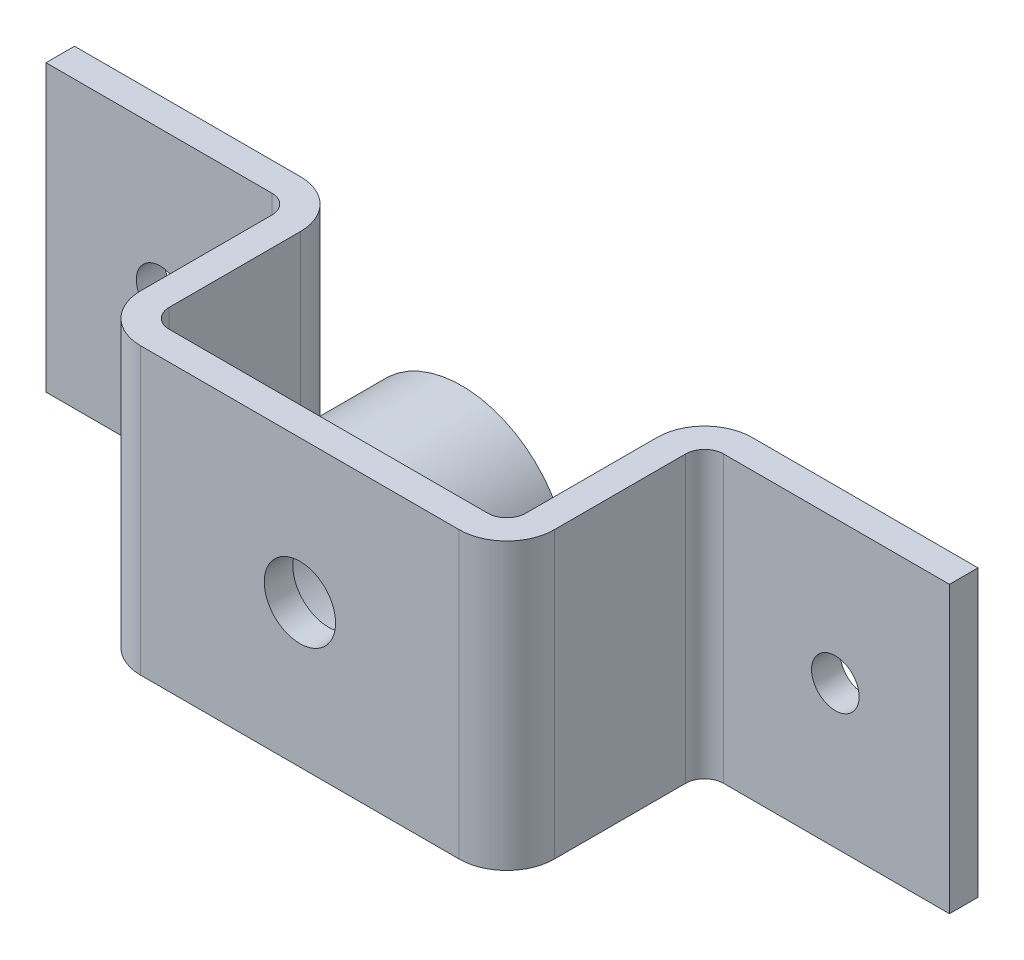
SolidWorks part; units mm, degrees
ref_plane "Front Plane" through (0, 0, 0) normal (0, 0, 1) x (1, 0, 0)
ref_plane "Top Plane" through (0, 0, 0) normal (0, 1, 0) x (1, 0, 0)
ref_plane "Right Plane" through (0, 0, 0) normal (1, 0, 0) x (0, 0, -1)
sketch "Sketch1" plane through (0, 0, 0) normal (0, 1, 0) x (1, 0, 0)
  line L0 (-609.8619, 0) -> (643.3786, 0) construction
  line L1 (0, 371.7017) -> (0, -371.7017) construction
  line L2 (-475, 0) -> (-237.5, 0)
  line L3 (-167.5, -208) -> (167.5, -208)
  line L4 (-187.5, -188) -> (-187.5, -50)
  line L5 (187.5, -188) -> (187.5, -50)
  line L6 (237.5, 0) -> (475, 0)
  line L7 (-475, -30) -> (-237.5, -30)
  line L8 (-217.5, -188) -> (-217.5, -50)
  line L9 (-167.5, -238) -> (167.5, -238)
  line L10 (217.5, -188) -> (217.5, -50)
  line L11 (237.5, -30) -> (475, -30)
  line L12 (-475, 0) -> (-475, -30)
  line L13 (475, 0) -> (475, -30)
  arc A0 (-187.5, -50) -> (-237.5, 0) centre (-237.5, -50) ccw
  arc A1 (187.5, -50) -> (237.5, 0) centre (237.5, -50) cw
  arc A2 (167.5, -208) -> (187.5, -188) centre (167.5, -188) ccw
  arc A3 (-167.5, -208) -> (-187.5, -188) centre (-167.5, -188) cw
  arc A4 (-217.5, -50) -> (-237.5, -30) centre (-237.5, -50) ccw
  arc A5 (-167.5, -238) -> (-217.5, -188) centre (-167.5, -188) cw
  arc A6 (167.5, -238) -> (217.5, -188) centre (167.5, -188) ccw
  arc A7 (217.5, -50) -> (237.5, -30) centre (237.5, -50) cw
  point P10 (0, -208)
  point P16 (187.5, 0)
  point P19 (187.5, -208)
  point P22 (-187.5, -208)
  dimension "D4" = 50
  dimension "D5" = 50
  dimension "D6" = 20
  dimension "D1" = 950
  dimension "D2" = 375
  dimension "D3" = 208
  dimension "D7" = 30
extrude "Boss-Extrude1" add sketch "Sketch1" along normal blind 300
sketch "Sketch2" plane through (0, 0, 208) normal (0, 0, -1) x (-1, 0, 0)
  line L0 (0, 435.8812) -> (0, -153.3317) construction
  line L1 (-475, 150) -> (475, 150) construction
  line L2 (-475, 300) -> (-475, 0) construction
  line L3 (475, 300) -> (475, 0) construction
  circle A0 centre (0, 150) radius 112.5
  dimension "D1" = 225
extrude "Boss-Extrude2" add sketch "Sketch2" along normal blind 140
sketch "Sketch3" plane through (0, 0, 68) normal (0, 0, -1) x (-1, 0, 0)
  circle A0 centre (0, 150) radius 87.5
  dimension "D1" = 175
extrude "Cut-Extrude1" cut sketch "Sketch3" against normal blind 140
sketch "Sketch4" plane through (0, 0, 208) normal (0, 0, -1) x (-1, 0, 0)
  circle A0 centre (0, 150) radius 37.5
  dimension "D1" = 75
extrude "Cut-Extrude2" cut sketch "Sketch4" against normal blind 140
sketch "Sketch5" plane through (0, 0, 0) normal (0, 0, -1) x (-1, 0, 0)
  line L0 (0, 488.2329) -> (0, -155.3847) construction
  line L1 (-475, 0) -> (-237.5, 0) construction
  line L2 (-475, 300) -> (-475, 0) construction
  circle A0 centre (-355, 150) radius 25
  circle A2 centre (355, 150) radius 25
  dimension "D1" = 50
  dimension "D2" = 150
  dimension "D3" = 120
extrude "Cut-Extrude3" cut sketch "Sketch5" against normal blind 140
